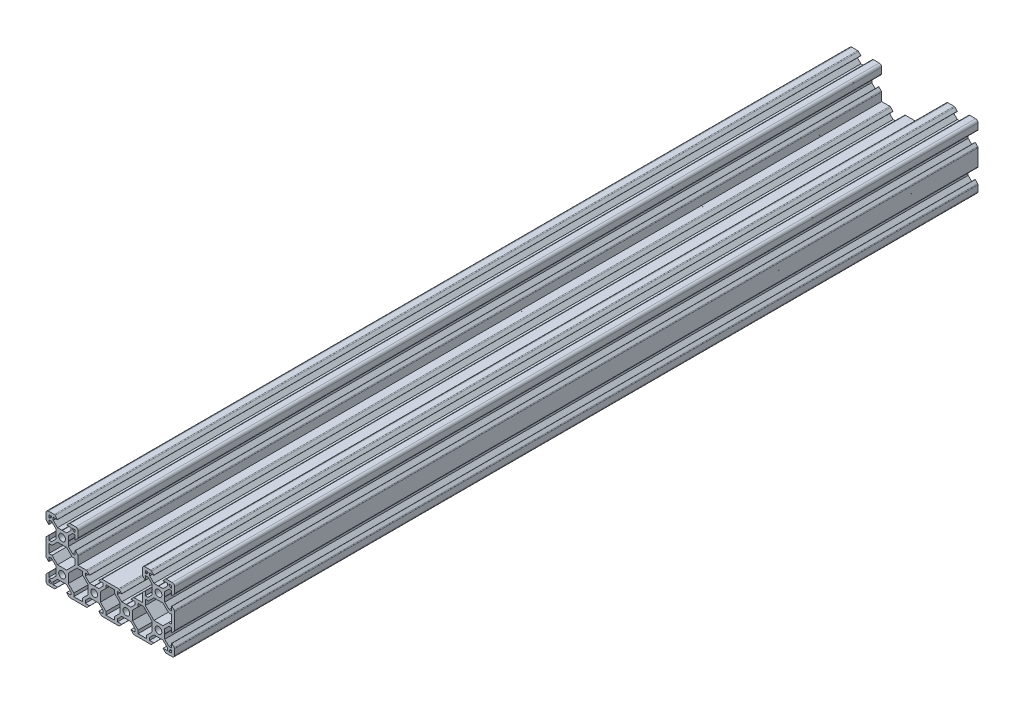
SolidWorks part; units mm, degrees
material "6063-T5"
ref_plane "Front Plane" through (0, 0, 0) normal (0, 0, 1) x (1, 0, 0)
ref_plane "Top Plane" through (0, 0, 0) normal (0, 1, 0) x (1, 0, 0)
ref_plane "Right Plane" through (0, 0, 0) normal (1, 0, 0) x (0, 0, -1)
sketch "Sketch3" plane through (0, 0, 0) normal (0, 0, 1) x (1, 0, 0)
  line L5 (-8.2, 2.8825) -> (-8.2, 5.4959)
  line L6 (-4.8999, 10.0096) -> (-8.496, 10.0096)
  line L14 (-10, 4.8997) -> (-10, 8.5056)
  line L18 (-999.9992, 0.0096) -> (49000.0008, 0.0096) construction
  line L19 (0, -999.9929) -> (0, 49000.0071) construction
  line L20 (-0.1067, 3.9071) -> (-2.835, 3.9071)
  line L22 (-3.9, 0.0983) -> (-3.9, 2.8367)
  line L24 (-2.8827, 8.208) -> (-5.496, 8.208)
  line L25 (-6.57, 8.208) -> (-6.57, 7.668)
  line L26 (-8.2, 6.578) -> (-7.66, 6.578)
  line L44 (-5.496, 8.208) -> (-5.496, 6.566)
  line L46 (-6.56, 5.4959) -> (-8.2, 5.4959)
  line L58 (30, -1000.0108) -> (30, 48999.9892) construction
  line L65 (-6.56, 5.4959) -> (-3.9, 2.8367)
  line L66 (-5.496, 6.566) -> (-2.835, 3.9071)
  line L67 (-7.66, 6.578) -> (-6.57, 7.668)
  line L68 (-8.2, 6.578) -> (-8.2, 8.208)
  line L69 (-6.57, 8.208) -> (-8.2, 8.208)
  line L70 (-2.8827, 8.3196) -> (-2.8827, 8.208)
  line L71 (-8.31, 2.8825) -> (-8.2, 2.8825)
  line L72 (-4.3413, 9.7782) -> (-2.8827, 8.3196)
  line L73 (-8.31, 2.8825) -> (-9.7686, 4.3411)
  line L74 (-0.1067, 3.9071) -> (0, 3.8071)
  line L75 (-3.9, 0.0983) -> (-3.7992, 0.0096)
  line L76 (-8.2, -7.2977) -> (-6.2381, -7.2977)
  line L77 (-8.31, -17.115) -> (-9.7657, -15.6593)
  line L78 (0, -3.9016) -> (-2.835, -3.9016)
  line L79 (-3.7992, 0.0096) -> (-3.9, -0.1033)
  line L80 (-3.9, -0.1033) -> (-3.9, -2.8417)
  line L81 (-2.835, -3.9016) -> (-6.2381, -7.2977)
  line L82 (-3.9, -2.8417) -> (-6.56, -5.4962)
  line L83 (-8.2, -2.8829) -> (-8.2, -5.4962)
  line L84 (-8.2, -17.115) -> (-8.31, -17.115)
  line L85 (-6.56, -5.4962) -> (-8.2, -5.4962)
  line L86 (10, -9.9904) -> (15.1019, -9.9904)
  line L87 (-8.2, -2.8829) -> (-8.31, -2.8829)
  line L88 (-8.31, -2.8829) -> (-9.7657, -4.3385)
  line L89 (-1000, -19.9904) -> (49000, -19.9904) construction
  line L90 (-8.2, -7.2977) -> (-8.2, -12.6899)
  line L91 (-10, -4.9042) -> (-10, -15.0936)
  line L92 (-6.56, -14.5017) -> (-8.2, -14.5017)
  line L93 (-8.2, -17.115) -> (-8.2, -14.5017)
  line L94 (-3.9, -17.1683) -> (-6.56, -14.5017)
  line L95 (-2.8404, -16.0895) -> (-6.24, -12.6899)
  line L96 (-3.9, -19.9066) -> (-3.9, -17.1683)
  line L97 (-3.8052, -20.0014) -> (-3.9, -19.9066)
  line L98 (0, -16.0895) -> (-2.8404, -16.0895)
  line L99 (-8.2, -12.6899) -> (-6.24, -12.6899)
  line L100 (-3.9, -20.0962) -> (-3.8052, -20.0014)
  line L101 (-0.0887, -23.8929) -> (0, -23.7929)
  line L102 (-8.31, -22.8804) -> (-9.7686, -24.339)
  line L103 (-4.334, -29.759) -> (-2.8754, -28.3004)
  line L104 (-8.31, -22.8804) -> (-8.2, -22.8804)
  line L105 (-2.8754, -28.3004) -> (-2.8754, -28.1904)
  line L106 (-6.57, -28.1904) -> (-8.2, -28.1904)
  line L107 (-8.2, -26.5604) -> (-8.2, -28.1904)
  line L108 (-7.66, -26.5604) -> (-6.57, -27.6504)
  line L109 (-5.4887, -26.5517) -> (-2.8291, -23.8929)
  line L110 (-6.56, -25.4937) -> (-3.9, -22.8345)
  line L111 (-6.56, -25.4937) -> (-8.2, -25.4937)
  line L112 (-5.4887, -28.1904) -> (-5.4887, -26.5517)
  line L113 (-8.2, -26.5604) -> (-7.66, -26.5604)
  line L114 (-6.57, -28.1904) -> (-6.57, -27.6504)
  line L115 (-2.8754, -28.1904) -> (-5.4887, -28.1904)
  line L116 (-3.9, -20.0962) -> (-3.9, -22.8345)
  line L117 (-0.0887, -23.8929) -> (-2.8291, -23.8929)
  line L118 (-10, -24.8976) -> (-10, -28.4904)
  line L119 (-4.9072, -29.9904) -> (-8.5, -29.9904)
  line L120 (-8.2, -22.8804) -> (-8.2, -25.4937)
  line L121 (20, -1019.9807) -> (20, 48980.0193) construction
  line L122 (-972.545, -9.9904) -> (49027.455, -9.9904) construction
  line L123 (-8.2, 2.8825) -> (-8.2, -2.8829) construction
  line L124 (-8.2, -17.115) -> (-8.2, -22.8804) construction
  line L125 (-2.8754, -28.1904) -> (2.89, -28.1904) construction
  line L126 (17.11, -28.1904) -> (22.8754, -28.1904) construction
  line L127 (17.1233, -11.7895) -> (22.8887, -11.7904) construction
  line L128 (8.2, -2.8829) -> (8.2, 2.8825) construction
  line L129 (2.8827, 8.208) -> (-2.8827, 8.208) construction
  line L130 (57.1173, 8.208) -> (62.8827, 8.208) construction
  line L131 (51.8, -2.8829) -> (51.8, 2.8825) construction
  line L132 (42.8767, -11.7895) -> (37.1113, -11.7904) construction
  line L133 (22.8482, -16.0895) -> (20.1099, -16.0895)
  line L134 (42.89, -28.1904) -> (37.1246, -28.1904) construction
  line L135 (62.8754, -28.1904) -> (57.11, -28.1904) construction
  line L136 (68.2, -17.115) -> (68.2, -22.8804) construction
  line L137 (68.2, 2.8825) -> (68.2, -2.8829) construction
  line L138 (51.8, 2.8825) -> (51.8, 5.4959)
  line L139 (55.1001, 10.0096) -> (51.504, 10.0096)
  line L140 (50, 4.8997) -> (50, 8.5056)
  line L141 (59.8933, 3.9071) -> (57.165, 3.9071)
  line L142 (56.1, 0.0983) -> (56.1, 2.8367)
  line L143 (57.1173, 8.208) -> (54.504, 8.208)
  line L144 (53.43, 8.208) -> (53.43, 7.668)
  line L145 (27.3193, -13.7504) -> (23.9096, -17.16)
  line L146 (22.8482, -16.0895) -> (25.5078, -13.4299)
  line L147 (51.8, 6.578) -> (52.34, 6.578)
  line L148 (54.504, 8.208) -> (54.504, 6.566)
  line L149 (53.44, 5.4959) -> (51.8, 5.4959)
  line L150 (53.44, 5.4959) -> (56.1, 2.8367)
  line L151 (54.504, 6.566) -> (57.165, 3.9071)
  line L152 (2.89, -28.1904) -> (5.5033, -28.1904)
  line L153 (22.8887, -11.7904) -> (22.8887, -11.6804)
  line L154 (5.5033, -26.5513) -> (5.5033, -28.1904)
  line L155 (24.3444, -10.2247) -> (22.8887, -11.6804)
  line L156 (7.3096, -26.2431) -> (7.3096, -28.1904)
  line L157 (2.89, -28.1904) -> (2.89, -28.3004)
  line L158 (2.89, -28.3004) -> (4.3457, -29.7561)
  line L159 (7.3096, -28.1904) -> (12.7, -28.1904)
  line L160 (16.1096, -17.16) -> (16.1096, -22.8307)
  line L161 (17.1705, -23.8929) -> (19.9105, -23.8929)
  line L162 (12.7, -26.2404) -> (16.1096, -22.8307)
  line L163 (17.1705, -23.8929) -> (14.4967, -26.5525)
  line L164 (17.11, -28.1904) -> (17.11, -28.3004)
  line L165 (4.9114, -29.9904) -> (15.0886, -29.9904)
  line L166 (15.6543, -29.7561) -> (17.11, -28.3004)
  line L167 (52.34, 6.578) -> (53.43, 7.668)
  line L168 (19.9105, -23.8929) -> (20.0109, -23.7929)
  line L169 (14.4967, -28.1904) -> (14.4967, -26.5525)
  line L170 (12.7, -28.1904) -> (12.7, -26.2404)
  line L171 (51.8, 6.578) -> (51.8, 8.208)
  line L172 (14.4967, -28.1904) -> (17.11, -28.1904)
  line L173 (20.1108, -23.8929) -> (20.0109, -23.7929)
  line L174 (25.502, -11.7904) -> (25.5078, -13.4299)
  line L175 (32.6807, -28.1904) -> (27.3193, -28.1904)
  line L176 (35.1033, -29.9904) -> (24.8967, -29.9904)
  line L177 (25.4887, -28.1904) -> (22.8754, -28.1904)
  line L178 (27.3193, -28.1904) -> (27.3193, -26.2304)
  line L179 (25.4887, -28.1904) -> (25.5159, -26.5596)
  line L180 (53.43, 8.208) -> (51.8, 8.208)
  line L181 (24.3311, -29.7561) -> (22.8754, -28.3004)
  line L182 (22.8754, -28.1904) -> (22.8754, -28.3004)
  line L183 (22.8492, -23.8929) -> (25.5159, -26.5596)
  line L184 (27.3193, -26.2304) -> (23.9096, -22.8207)
  line L185 (22.8492, -23.8929) -> (20.1108, -23.8929)
  line L186 (23.9096, -17.16) -> (23.9096, -22.8207)
  line L187 (27.3193, -11.7904) -> (27.3193, -13.7504)
  line L188 (25.502, -11.7904) -> (22.8887, -11.7904)
  line L189 (35.0899, -9.9904) -> (24.9101, -9.9904)
  line L190 (32.6807, -11.7904) -> (27.3193, -11.7904)
  line L191 (20.1099, -16.0895) -> (20.0097, -16.1897)
  line L192 (14.51, -11.7895) -> (17.1233, -11.7895)
  line L193 (12.7, -11.7987) -> (12.7, -13.7504)
  line L194 (14.51, -11.7895) -> (14.51, -13.4299)
  line L195 (19.9096, -16.0895) -> (20.0097, -16.1897)
  line L196 (0.0887, -23.8929) -> (2.8291, -23.8929)
  line L197 (15.6676, -10.2297) -> (17.1233, -11.6854)
  line L198 (57.1173, 8.3196) -> (57.1173, 8.208)
  line L199 (17.1233, -11.7895) -> (17.1233, -11.6854)
  line L200 (17.1696, -16.0895) -> (14.51, -13.4299)
  line L201 (12.7, -13.7504) -> (16.1096, -17.16)
  line L202 (17.1696, -16.0895) -> (19.9096, -16.0895)
  line L203 (51.69, 2.8825) -> (51.8, 2.8825)
  line L204 (9.2696, -11.7987) -> (12.7, -11.7987)
  line L205 (55.6587, 9.7782) -> (57.1173, 8.3196)
  line L206 (51.69, 2.8825) -> (50.2314, 4.3411)
  line L207 (59.8933, 3.9071) -> (60, 3.8071)
  line L208 (56.1, 0.0983) -> (56.2008, 0.0096)
  line L209 (51.8, -7.2977) -> (53.7619, -7.2977)
  line L210 (2.84, -16.0895) -> (8.2, -10.7295)
  line L211 (60, -3.9016) -> (57.165, -3.9016)
  line L212 (56.2008, 0.0096) -> (56.1, -0.1033)
  line L213 (56.1, -0.1033) -> (56.1, -2.8417)
  line L214 (57.165, -3.9016) -> (53.7619, -7.2977)
  line L215 (56.1, -2.8417) -> (53.44, -5.4962)
  line L216 (51.8, -2.8829) -> (51.8, -5.4962)
  line L217 (53.44, -5.4962) -> (51.8, -5.4962)
  line L218 (51.8, -2.8829) -> (51.69, -2.8829)
  line L219 (51.69, -2.8829) -> (50.2343, -4.3385)
  line L220 (51.8, -7.2977) -> (51.8, -10.7295)
  line L221 (50, -4.9042) -> (50, -9.9904)
  line L222 (56.1, -17.1683) -> (50.7304, -11.7987)
  line L223 (56.1, -22.8345) -> (56.1, -17.1683)
  line L224 (60, -16.0895) -> (57.16, -16.0895)
  line L225 (59.9113, -23.8929) -> (60, -23.7929)
  line L226 (54.4967, -26.5513) -> (57.1709, -23.8929)
  line L227 (52.6904, -26.2431) -> (56.1, -22.8345)
  line L228 (57.16, -16.0895) -> (51.8, -10.7295)
  line L229 (50.7304, -11.7987) -> (47.3, -11.7987)
  line L230 (42.8304, -16.0895) -> (40.0904, -16.0895)
  line L231 (47.3, -13.7504) -> (43.8904, -17.16)
  line L232 (42.8304, -16.0895) -> (45.49, -13.4299)
  line L233 (42.8767, -11.7895) -> (42.8767, -11.6854)
  line L234 (44.3324, -10.2297) -> (42.8767, -11.6854)
  line L235 (59.9113, -23.8929) -> (57.1709, -23.8929)
  line L236 (40.0904, -16.0895) -> (39.9903, -16.1897)
  line L237 (45.49, -11.7895) -> (45.49, -13.4299)
  line L238 (47.3, -11.7987) -> (47.3, -13.7504)
  line L239 (45.49, -11.7895) -> (42.8767, -11.7895)
  line L240 (39.8901, -16.0895) -> (39.9903, -16.1897)
  line L241 (34.498, -11.7904) -> (37.1113, -11.7904)
  line L242 (32.6807, -11.7904) -> (32.6807, -13.7504)
  line L243 (36.0904, -17.16) -> (36.0904, -22.8207)
  line L244 (37.1508, -23.8929) -> (39.8892, -23.8929)
  line L245 (32.6807, -26.2304) -> (36.0904, -22.8207)
  line L246 (37.1508, -23.8929) -> (34.4841, -26.5596)
  line L247 (37.1246, -28.1904) -> (37.1246, -28.3004)
  line L248 (35.6689, -29.7561) -> (37.1246, -28.3004)
  line L249 (34.5113, -28.1904) -> (34.4841, -26.5596)
  line L250 (32.6807, -28.1904) -> (32.6807, -26.2304)
  line L251 (34.5113, -28.1904) -> (37.1246, -28.1904)
  line L252 (34.498, -11.7904) -> (34.4922, -13.4299)
  line L253 (39.8892, -23.8929) -> (39.9891, -23.7929)
  line L254 (45.5033, -28.1904) -> (42.89, -28.1904)
  line L255 (47.3, -28.1904) -> (47.3, -26.2404)
  line L256 (45.5033, -28.1904) -> (45.5033, -26.5525)
  line L257 (40.0895, -23.8929) -> (39.9891, -23.7929)
  line L258 (44.3457, -29.7561) -> (42.89, -28.3004)
  line L259 (55.0886, -29.9904) -> (44.9114, -29.9904)
  line L260 (42.89, -28.1904) -> (42.89, -28.3004)
  line L261 (42.8295, -23.8929) -> (45.5033, -26.5525)
  line L262 (47.3, -26.2404) -> (43.8904, -22.8307)
  line L263 (42.8295, -23.8929) -> (40.0895, -23.8929)
  line L264 (43.8904, -17.16) -> (43.8904, -22.8307)
  line L265 (52.6904, -28.1904) -> (47.3, -28.1904)
  line L266 (57.11, -28.3004) -> (55.6543, -29.7561)
  line L267 (57.11, -28.1904) -> (57.11, -28.3004)
  line L268 (52.6904, -26.2431) -> (52.6904, -28.1904)
  line L269 (35.6556, -10.2247) -> (37.1113, -11.6804)
  line L270 (54.4967, -26.5513) -> (54.4967, -28.1904)
  line L271 (37.1113, -11.7904) -> (37.1113, -11.6804)
  line L272 (57.11, -28.1904) -> (54.4967, -28.1904)
  line L273 (37.1518, -16.0895) -> (34.4922, -13.4299)
  line L274 (32.6807, -13.7504) -> (36.0904, -17.16)
  line L275 (37.1518, -16.0895) -> (39.8901, -16.0895)
  line L276 (68.2, -22.8804) -> (68.2, -25.4937)
  line L277 (64.9072, -29.9904) -> (68.5, -29.9904)
  line L278 (70, -24.8976) -> (70, -28.4904)
  line L279 (60.0887, -23.8929) -> (62.8291, -23.8929)
  line L280 (63.9, -20.0962) -> (63.9, -22.8345)
  line L281 (62.8754, -28.1904) -> (65.4887, -28.1904)
  line L282 (66.57, -28.1904) -> (66.57, -27.6504)
  line L283 (68.2, -26.5604) -> (67.66, -26.5604)
  line L284 (65.4887, -28.1904) -> (65.4887, -26.5517)
  line L285 (66.56, -25.4937) -> (68.2, -25.4937)
  line L286 (66.56, -25.4937) -> (63.9, -22.8345)
  line L287 (65.4887, -26.5517) -> (62.8291, -23.8929)
  line L288 (67.66, -26.5604) -> (66.57, -27.6504)
  line L289 (68.2, -26.5604) -> (68.2, -28.1904)
  line L290 (66.57, -28.1904) -> (68.2, -28.1904)
  line L291 (62.8754, -28.3004) -> (62.8754, -28.1904)
  line L292 (68.31, -22.8804) -> (68.2, -22.8804)
  line L293 (64.334, -29.759) -> (62.8754, -28.3004)
  line L294 (68.31, -22.8804) -> (69.7686, -24.339)
  line L295 (60.0887, -23.8929) -> (60, -23.7929)
  line L296 (63.9, -20.0962) -> (63.8052, -20.0014)
  line L297 (68.2, -12.6899) -> (66.24, -12.6899)
  line L298 (60, -16.0895) -> (62.8404, -16.0895)
  line L299 (63.8052, -20.0014) -> (63.9, -19.9066)
  line L300 (63.9, -19.9066) -> (63.9, -17.1683)
  line L301 (62.8404, -16.0895) -> (66.24, -12.6899)
  line L302 (63.9, -17.1683) -> (66.56, -14.5017)
  line L303 (68.2, -17.115) -> (68.2, -14.5017)
  line L304 (66.56, -14.5017) -> (68.2, -14.5017)
  line L305 (70, -4.9042) -> (70, -15.0936)
  line L306 (68.2, -7.2977) -> (68.2, -12.6899)
  line L307 (68.31, -2.8829) -> (69.7657, -4.3385)
  line L308 (68.2, -2.8829) -> (68.31, -2.8829)
  line L309 (50, -9.9904) -> (44.8981, -9.9904)
  line L310 (66.56, -5.4962) -> (68.2, -5.4962)
  line L311 (68.2, -17.115) -> (68.31, -17.115)
  line L312 (68.2, -2.8829) -> (68.2, -5.4962)
  line L313 (63.9, -2.8417) -> (66.56, -5.4962)
  line L314 (62.835, -3.9016) -> (66.2381, -7.2977)
  line L315 (63.9, -0.1033) -> (63.9, -2.8417)
  line L316 (63.7992, 0.0096) -> (63.9, -0.1033)
  line L317 (60, -3.9016) -> (62.835, -3.9016)
  line L318 (68.31, -17.115) -> (69.7657, -15.6593)
  line L319 (68.2, -7.2977) -> (66.2381, -7.2977)
  line L320 (63.9, 0.0983) -> (63.7992, 0.0096)
  line L321 (60.1067, 3.9071) -> (60, 3.8071)
  line L322 (68.31, 2.8825) -> (69.7686, 4.3411)
  line L323 (64.3413, 9.7782) -> (62.8827, 8.3196)
  line L324 (68.31, 2.8825) -> (68.2, 2.8825)
  line L325 (62.8827, 8.3196) -> (62.8827, 8.208)
  line L326 (66.57, 8.208) -> (68.2, 8.208)
  line L327 (68.2, 6.578) -> (68.2, 8.208)
  line L328 (67.66, 6.578) -> (66.57, 7.668)
  line L329 (65.496, 6.566) -> (62.835, 3.9071)
  line L330 (66.56, 5.4959) -> (63.9, 2.8367)
  line L331 (66.56, 5.4959) -> (68.2, 5.4959)
  line L332 (65.496, 8.208) -> (65.496, 6.566)
  line L333 (68.2, 6.578) -> (67.66, 6.578)
  line L334 (66.57, 8.208) -> (66.57, 7.668)
  line L335 (62.8827, 8.208) -> (65.496, 8.208)
  line L336 (63.9, 0.0983) -> (63.9, 2.8367)
  line L337 (60.1067, 3.9071) -> (62.835, 3.9071)
  line L338 (70, 4.8997) -> (70, 8.5056)
  line L339 (64.8999, 10.0096) -> (68.496, 10.0096)
  line L340 (68.2, 2.8825) -> (68.2, 5.4959)
  line L347 (7.3096, -26.2431) -> (3.9, -22.8345)
  line L348 (5.5033, -26.5513) -> (2.8291, -23.8929)
  line L356 (0.0887, -23.8929) -> (0, -23.7929)
  line L359 (0, -16.0895) -> (2.84, -16.0895)
  line L361 (3.9, -22.8345) -> (3.9, -17.1683)
  line L363 (3.9, -17.1683) -> (9.2696, -11.7987)
  line L366 (10, -4.9042) -> (10, -9.9904)
  line L367 (8.2, -7.2977) -> (8.2, -10.7295)
  line L369 (8.31, -2.8829) -> (9.7657, -4.3385)
  line L370 (8.2, -2.8829) -> (8.31, -2.8829)
  line L372 (6.56, -5.4962) -> (8.2, -5.4962)
  line L374 (8.2, -2.8829) -> (8.2, -5.4962)
  line L375 (3.9, -2.8417) -> (6.56, -5.4962)
  line L376 (2.835, -3.9016) -> (6.2381, -7.2977)
  line L377 (3.9, -0.1033) -> (3.9, -2.8417)
  line L378 (3.7992, 0.0096) -> (3.9, -0.1033)
  line L379 (0, -3.9016) -> (2.835, -3.9016)
  line L381 (8.2, -7.2977) -> (6.2381, -7.2977)
  line L382 (3.9, 0.0983) -> (3.7992, 0.0096)
  line L383 (0.1067, 3.9071) -> (0, 3.8071)
  line L384 (8.31, 2.8825) -> (9.7686, 4.3411)
  line L385 (4.3413, 9.7782) -> (2.8827, 8.3196)
  line L386 (8.31, 2.8825) -> (8.2, 2.8825)
  line L387 (2.8827, 8.3196) -> (2.8827, 8.208)
  line L388 (6.57, 8.208) -> (8.2, 8.208)
  line L389 (8.2, 6.578) -> (8.2, 8.208)
  line L390 (7.66, 6.578) -> (6.57, 7.668)
  line L391 (5.496, 6.566) -> (2.835, 3.9071)
  line L392 (6.56, 5.4959) -> (3.9, 2.8367)
  line L393 (6.56, 5.4959) -> (8.2, 5.4959)
  line L394 (5.496, 8.208) -> (5.496, 6.566)
  line L395 (8.2, 6.578) -> (7.66, 6.578)
  line L396 (6.57, 8.208) -> (6.57, 7.668)
  line L397 (2.8827, 8.208) -> (5.496, 8.208)
  line L398 (3.9, 0.0983) -> (3.9, 2.8367)
  line L399 (0.1067, 3.9071) -> (2.835, 3.9071)
  line L400 (10, 4.8997) -> (10, 8.5056)
  line L401 (4.8999, 10.0096) -> (8.496, 10.0096)
  line L402 (8.2, 2.8825) -> (8.2, 5.4959)
  arc A6 (-10, 8.5056) -> (-8.496, 10.0096) centre (-8.496, 8.5056) cw
  arc A7 (-9.7686, 4.3411) -> (-10, 4.8997) centre (-9.21, 4.8997) cw
  arc A8 (-4.3413, 9.7782) -> (-4.8999, 10.0096) centre (-4.8999, 9.2196) ccw
  arc A9 (-9.7657, -4.3385) -> (-10, -4.9042) centre (-9.2, -4.9042) ccw
  circle A10 centre (0, 0.0096) radius 2.1
  circle A11 centre (0, -19.9904) radius 2.1
  arc A12 (-9.7657, -15.6593) -> (-10, -15.0936) centre (-9.2, -15.0936) cw
  arc A13 (-4.334, -29.759) -> (-4.9072, -29.9904) centre (-4.8927, -29.2005) cw
  arc A14 (-9.7686, -24.339) -> (-10, -24.8976) centre (-9.21, -24.8976) ccw
  arc A15 (-10, -28.4904) -> (-8.5, -29.9904) centre (-8.5, -28.4904) ccw
  circle A16 centre (20, -19.9904) radius 2.1
  arc A17 (50, 8.5056) -> (51.504, 10.0096) centre (51.504, 8.5056) cw
  arc A18 (50.2314, 4.3411) -> (50, 4.8997) centre (50.79, 4.8997) cw
  arc A19 (55.6587, 9.7782) -> (55.1001, 10.0096) centre (55.1001, 9.2196) ccw
  arc A20 (15.6543, -29.7561) -> (15.0886, -29.9904) centre (15.0886, -29.1904) cw
  arc A21 (4.3457, -29.7561) -> (4.9114, -29.9904) centre (4.9114, -29.1904) ccw
  arc A22 (50.2343, -4.3385) -> (50, -4.9042) centre (50.8, -4.9042) ccw
  arc A23 (24.3311, -29.7561) -> (24.8967, -29.9904) centre (24.8967, -29.1904) ccw
  arc A24 (24.3444, -10.2247) -> (24.9101, -9.9904) centre (24.9101, -10.7904) cw
  arc A25 (44.3324, -10.2297) -> (44.8981, -9.9904) centre (44.903, -10.7903) cw
  arc A26 (35.6556, -10.2247) -> (35.0899, -9.9904) centre (35.0899, -10.7904) ccw
  arc A27 (15.6676, -10.2297) -> (15.1019, -9.9904) centre (15.097, -10.7903) ccw
  arc A28 (35.6689, -29.7561) -> (35.1033, -29.9904) centre (35.1033, -29.1904) cw
  arc A29 (55.6543, -29.7561) -> (55.0886, -29.9904) centre (55.0886, -29.1904) cw
  arc A30 (44.3457, -29.7561) -> (44.9114, -29.9904) centre (44.9114, -29.1904) ccw
  circle A31 centre (40, -19.9904) radius 2.1
  arc A32 (70, -28.4904) -> (68.5, -29.9904) centre (68.5, -28.4904) cw
  arc A33 (69.7686, -24.339) -> (70, -24.8976) centre (69.21, -24.8976) cw
  arc A34 (64.334, -29.759) -> (64.9072, -29.9904) centre (64.8927, -29.2005) ccw
  arc A35 (69.7657, -15.6593) -> (70, -15.0936) centre (69.2, -15.0936) ccw
  circle A36 centre (60, -19.9904) radius 2.1
  circle A37 centre (60, 0.0096) radius 2.1
  arc A38 (69.7657, -4.3385) -> (70, -4.9042) centre (69.2, -4.9042) cw
  arc A39 (64.3413, 9.7782) -> (64.8999, 10.0096) centre (64.8999, 9.2196) cw
  arc A40 (69.7686, 4.3411) -> (70, 4.8997) centre (69.21, 4.8997) ccw
  arc A41 (70, 8.5056) -> (68.496, 10.0096) centre (68.496, 8.5056) ccw
  arc A52 (9.7657, -4.3385) -> (10, -4.9042) centre (9.2, -4.9042) cw
  arc A53 (4.3413, 9.7782) -> (4.8999, 10.0096) centre (4.8999, 9.2196) cw
  arc A54 (9.7686, 4.3411) -> (10, 4.8997) centre (9.21, 4.8997) ccw
  arc A55 (10, 8.5056) -> (8.496, 10.0096) centre (8.496, 8.5056) ccw
  point P68 (-10, -9.9989)
  point P69 (-8.2, -9.9938)
  point P107 (30, -9.9904)
  point P109 (30, -28.1904)
  point P116 (30, -9.9904)
  point P171 (30, -28.1904)
  point P215 (30, -9.9904)
  point P295 (30, -11.7904)
  point P306 (30, -29.9904)
  point P346 (30, -11.7904)
  point P360 (30, -29.9904)
  point P371 (30, -29.9904)
  point P372 (30, -11.7904)
  point P373 (30, -28.1904)
  point P374 (68.2, -9.9938)
  point P375 (70, -9.9989)
  dimension "D3" = 10
  dimension "D15" = 20
  dimension "D7" = 4.2
  dimension "D12" = 20
  dimension "D10" = 10
  dimension "D4" = 10
  dimension "D9" = 20
  dimension "D16" = 20
  dimension "D1" = 30
  dimension "D2" = 40
  dimension "D5" = 20
  dimension "D6" = 20
  dimension "D8" = 20
  dimension "D11" = 10
  dimension "D13" = 80
  dimension "D14" = 40
extrude "Boss-Extrude3" add sketch "Sketch3" along normal blind 500
